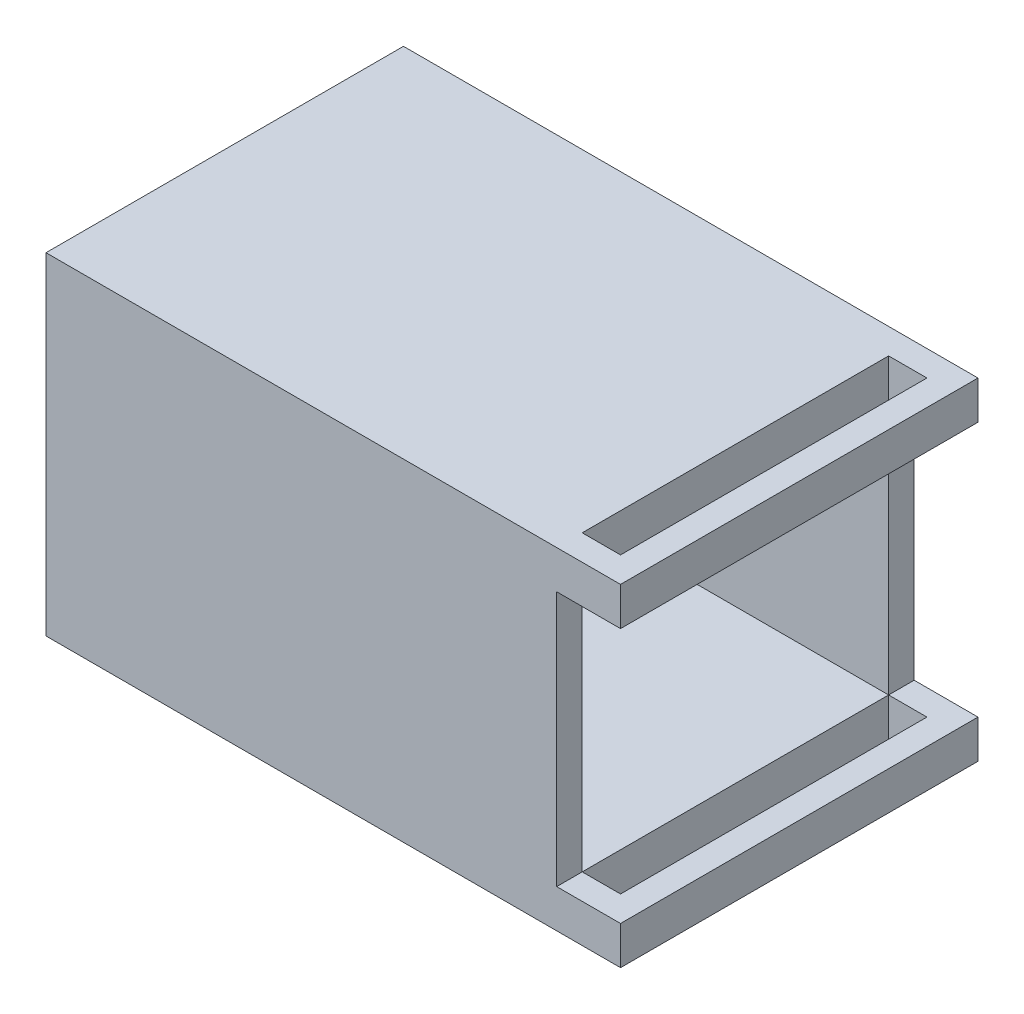
SolidWorks part; units mm, degrees
ref_plane "Front Plane" through (0, 0, 0) normal (0, 0, 1) x (1, 0, 0)
ref_plane "Top Plane" through (0, 0, 0) normal (0, 1, 0) x (1, 0, 0)
ref_plane "Right Plane" through (0, 0, 0) normal (1, 0, 0) x (0, 0, -1)
sketch "Sketch1" plane through (0, 0, 0) normal (0, 1, 0) x (1, 0, 0)
  line L1 (0, 0) -> (45, 0)
  line L2 (0, 0) -> (0, 28)
  line L3 (0, 28) -> (45, 28)
  line L4 (45, 0) -> (45, 28)
  dimension "D1" = 28
  dimension "D2" = 45
extrude "Boss-Extrude1" add sketch "Sketch1" along normal blind 3 contours L2 L1 L4 L3
sketch "Sketch2" plane through (0, 3, 0) normal (0, 1, 0) x (1, 0, 0)
  line L0 (40, 26) -> (40, 28)
  line L1 (0, 28) -> (40, 28)
  line L2 (0, 28) -> (0, 0)
  line L3 (0, 0) -> (40, 0)
  line L5 (2, 26) -> (40, 26)
  line L6 (2, 26) -> (2, 2)
  line L7 (2, 2) -> (40, 2)
  line L9 (40, 2) -> (40, 0)
  line L10 (45, 0) -> (45, 28) construction
  line L11 (0, 0) -> (45, 0) construction
  dimension "D1" = 2
  dimension "D2" = 2
  dimension "D3" = 2
  dimension "D4" = 5
  dimension "D5" = 5
extrude "Boss-Extrude2" add sketch "Sketch2" along normal blind 22 contours L5 L0 L1 L2 L3 L9 L7 L6
sketch "Sketch4" plane through (0, 25, 0) normal (0, 1, 0) x (1, 0, 0)
  line L0 (0, 28) -> (40, 28) construction
  line L1 (0, 28) -> (45, 28)
  line L2 (0, 28) -> (0, 0)
  line L3 (0, 0) -> (45, 0)
  line L4 (45, 28) -> (45, 0)
  line L5 (2, 2) -> (40, 2) construction
  line L6 (40, 26) -> (43, 26)
  line L7 (40, 26) -> (40, 2)
  line L8 (40, 2) -> (43, 2)
  line L9 (43, 26) -> (43, 2)
  dimension "D1" = 2
extrude "Boss-Extrude4" add sketch "Sketch4" against normal blind 2
sketch "Sketch5" plane through (0, 0, 0) normal (-1, 0, 0) x (0, 0, 1)
  line L0 (-18.72, 5.25) -> (-18.72, 5.96)
  line L1 (-17.47, 4) -> (-10.53, 4)
  line L2 (-17.47, 7.21) -> (-10.53, 7.21)
  line L3 (-9.28, 5.96) -> (-9.28, 5.25)
  line L4 (0, 0) -> (-28, 0) construction
  line L5 (-28, 25) -> (-28, 0) construction
  line L6 (0, 25) -> (0, 0) construction
  line L7 (-18.5, 12.5) -> (-9.5, 12.5)
  line L8 (-18.5, 12.5) -> (-18.5, 8.5)
  line L9 (-18.5, 8.5) -> (-9.5, 8.5)
  line L10 (-9.5, 12.5) -> (-9.5, 8.5)
  arc A0 (-18.72, 5.25) -> (-17.47, 4) centre (-17.47, 5.25) ccw
  arc A1 (-17.47, 7.21) -> (-18.72, 5.96) centre (-17.47, 5.96) ccw
  arc A2 (-9.28, 5.96) -> (-10.53, 7.21) centre (-10.53, 5.96) ccw
  arc A3 (-10.53, 4) -> (-9.28, 5.25) centre (-10.53, 5.25) ccw
  dimension "D7" = 1.25
  dimension "D1" = 1.25
  dimension "D2" = 0.71
  dimension "D3" = 6.94
  dimension "D4" = 1.25
  dimension "D5" = 1.25
  dimension "D6" = 6.94
  dimension "D8" = 3.21
  dimension "D9" = 0.71
  dimension "D10" = 4
  dimension "D11" = 9.28
  dimension "D12" = 4
  dimension "D13" = 9
  dimension "D14" = 1.29
  dimension "D15" = 0.22
  dimension "D16" = 0.22
  dimension "D17" = 9.28
extrude "Cut-Extrude1" cut sketch "Sketch5" against normal blind 2
sketch "Sketch6" plane through (0, 3, 0) normal (0, 1, 0) x (1, 0, 0)
  line L0 (45, 0) -> (45, 28) construction
  line L1 (43, 2) -> (40, 2)
  line L2 (43, 2) -> (43, 26)
  line L3 (43, 26) -> (40, 26)
  line L4 (40, 2) -> (40, 26)
  line L5 (40, 0) -> (45, 0) construction
  line L6 (40, 28) -> (45, 28) construction
  line L7 (40, 26) -> (40, 28) construction
  dimension "D1" = 2
  dimension "D2" = 2
  dimension "D3" = 2
extrude "Cut-Extrude2" cut sketch "Sketch6" against normal blind 3
sketch "Sketch7" plane through (0, 25, 0) normal (0, 1, 0) x (1, 0, 0)
  line L1 (0, 0) -> (45, 0)
  line L2 (0, 0) -> (0, 28)
  line L3 (0, 28) -> (45, 28)
  line L4 (45, 0) -> (45, 28)
  line L5 (40, 26) -> (43, 26)
  line L6 (40, 26) -> (40, 2)
  line L7 (40, 2) -> (43, 2)
  line L8 (43, 26) -> (43, 2)
extrude "Boss-Extrude5" add sketch "Sketch7" along normal blind 1
